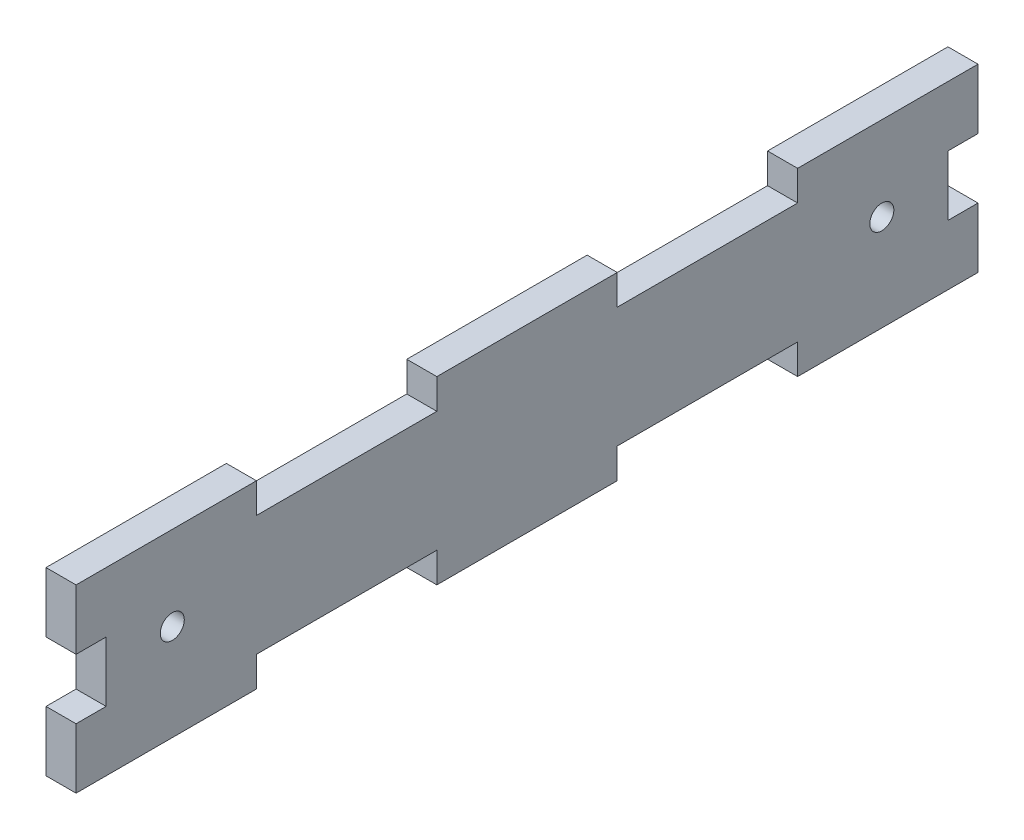
SolidWorks part; units mm, degrees
ref_plane "Alzado" through (0, 0, 0) normal (0, 0, 1) x (1, 0, 0)
ref_plane "Planta" through (0, 0, 0) normal (0, 1, 0) x (1, 0, 0)
ref_plane "Vista lateral" through (0, 0, 0) normal (1, 0, 0) x (0, 0, -1)
sketch "Croquis1" plane through (0, 0, 0) normal (1, 0, 0) x (0, 0, -1)
  line L0 (0, 20) -> (5, 20)
  line L1 (0, 0) -> (30, 0)
  line L2 (0, 0) -> (0, 10)
  line L3 (0, 30) -> (30, 30)
  line L4 (150, 0) -> (150, 10)
  line L5 (5, 20) -> (5, 10)
  line L6 (5, 10) -> (0, 10)
  line L7 (75, 40) -> (75, 31.2401) construction
  line L8 (145, 10) -> (150, 10)
  line L9 (145, 20) -> (145, 10)
  line L10 (150, 20) -> (145, 20)
  line L11 (30, 0) -> (30, 5)
  line L12 (30, 5) -> (60, 5)
  line L13 (60, 5) -> (60, 0)
  line L14 (120, 0) -> (120, 5)
  line L15 (90, 5) -> (90, 0)
  line L16 (120, 5) -> (90, 5)
  line L17 (5, 15) -> (8.4564, 15) construction
  line L18 (120, 30) -> (120, 25)
  line L19 (120, 25) -> (90, 25)
  line L20 (90, 25) -> (90, 30)
  line L21 (60, 25) -> (60, 30)
  line L22 (30, 30) -> (30, 25)
  line L23 (30, 25) -> (60, 25)
  line L24 (0, 20) -> (0, 30)
  line L25 (60, 30) -> (90, 30)
  line L26 (60, 0) -> (90, 0)
  line L27 (120, 0) -> (150, 0)
  line L28 (120, 30) -> (150, 30)
  line L29 (150, 20) -> (150, 30)
  circle A0 centre (16, 16) radius 2
  circle A1 centre (134, 16) radius 2
  dimension "D4" = 4
  dimension "D1" = 150
  dimension "D2" = 30
  dimension "D3" = 5
  dimension "D5" = 10
  dimension "D6" = 30
  dimension "D7" = 30
  dimension "D8" = 5
  dimension "D9" = 16
  dimension "D10" = 16
extrude "Saliente-Extruir1" add sketch "Croquis1" along normal blind 5
